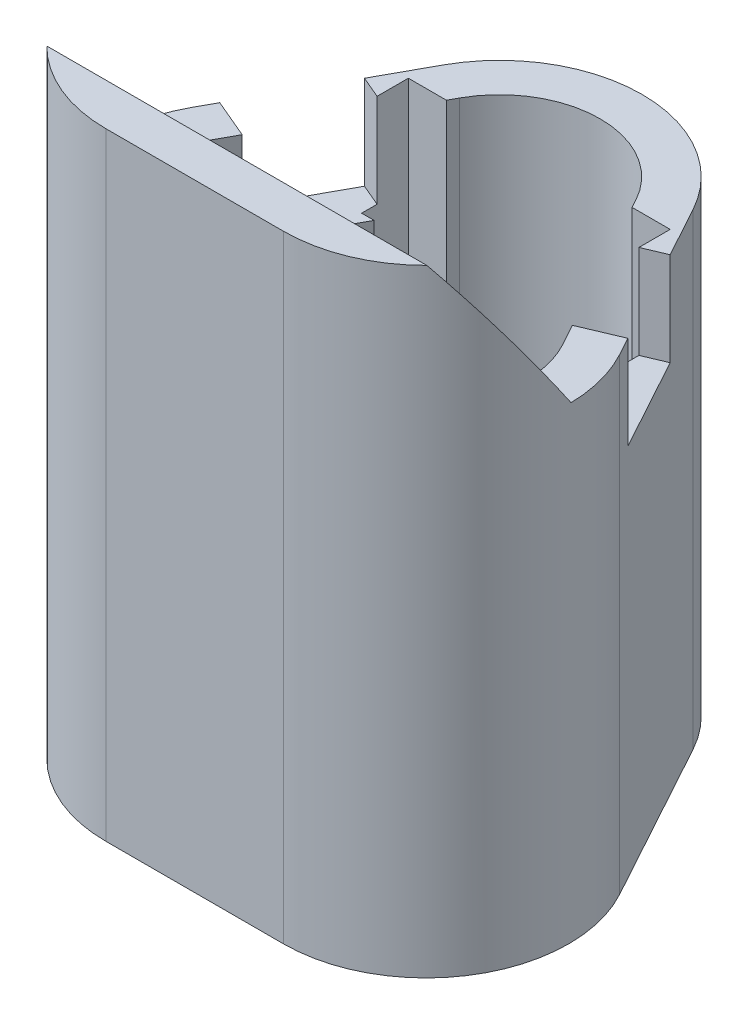
SolidWorks part; units mm, degrees
ref_plane "Plano frontal" through (0, 0, 0) normal (0, 0, 1) x (1, 0, 0)
ref_plane "Plano superior" through (0, 0, 0) normal (0, 1, 0) x (1, 0, 0)
ref_plane "Plano direito" through (0, 0, 0) normal (1, 0, 0) x (0, 0, -1)
sketch "Esboço1" plane through (0, 0, 0) normal (0, 1, 0) x (1, 0, 0)
  line L7 (-13.3761, 16.0541) -> (-22.8761, -1.2959)
  line L8 (13.3761, 16.0541) -> (22.8761, -1.2959)
  line L9 (-9.5, -23.87) -> (9.5, -23.87)
  arc A1 (-22.8761, -1.2959) -> (-9.5, -23.87) centre (-9.5, -8.62) ccw
  arc A3 (9.5, -23.87) -> (22.8761, -1.2959) centre (9.5, -8.62) ccw
  arc A5 (13.3761, 16.0541) -> (-13.3761, 16.0541) centre (0, 8.73) ccw
extrude "Ressalto-extrusão1" add sketch "Esboço1" along normal blind 66 contours L7 A1 L9 A3 L8 A5
sketch "Esboço2" plane through (0, 66, 0) normal (0, 1, 0) x (1, 0, 0)
  line L0 (-18.9291, -3.4571) -> (-9.4291, 13.8929)
  line L1 (18.9291, -3.4571) -> (9.4291, 13.8929)
  line L2 (-9.5, -19.37) -> (9.5, -19.37)
  arc A4 (-18.9291, -3.4571) -> (-9.5, -19.37) centre (-9.5, -8.62) ccw
  arc A6 (9.5, -19.37) -> (18.9291, -3.4571) centre (9.5, -8.62) ccw
  arc A9 (9.4291, 13.8929) -> (-9.4291, 13.8929) centre (0, 8.73) ccw
extrude "Corte-extrusão1" cut sketch "Esboço2" against normal blind 53.5
sketch "Esboço3" plane through (0, 66, 0) normal (0, 1, 0) x (1, 0, 0)
  line L2 (0, -3.37) -> (18.8814, -3.37)
  line L3 (0, -3.37) -> (-18.8814, -3.37)
  line L4 (-9.4291, 13.8929) -> (-18.8814, -3.37)
  line L5 (18.8814, -3.37) -> (9.4291, 13.8929)
  arc A3 (9.4291, 13.8929) -> (-9.4291, 13.8929) centre (0, 8.73) ccw
extrude "Corte-extrusão2" cut sketch "Esboço3" against normal blind 63
sketch "Esboço4" plane through (0, 0, 0) normal (1, 0, 0) x (0, 0, -1)
  line L0 (-8.37, 50) -> (35.3375, 50)
  line L6 (-19.37, 66) -> (-19.37, 68.6327)
  line L7 (-19.37, 68.6327) -> (33.499, 68.6327)
  line L8 (33.499, 68.6327) -> (35.3375, 50)
  line L9 (-19.37, 66) -> (-8.37, 50)
extrude "Corte-extrusão3" cut sketch "Esboço4" against normal through all both and the other way through all
sketch "Esboço5" plane through (0, 50, 0) normal (0, 1, 0) x (1, 0, 0)
  line L2 (5, 11.13) -> (7, 11.13)
  line L3 (7, 11.13) -> (7, 3.13)
  line L4 (7, 3.13) -> (5, 3.13)
  line L5 (5, 3.13) -> (5, 11.13)
  line L7 (-5, 11.13) -> (-5, 3.13)
  line L8 (-5, 3.13) -> (-7, 3.13)
  line L9 (-7, 3.13) -> (-7, 11.13)
  line L10 (-5, 11.13) -> (-7, 11.13)
extrude "Corte-extrusão4" cut sketch "Esboço5" against normal through all both
sketch "Esboço6" plane through (0, 50, 0) normal (0, 1, 0) x (1, 0, 0)
  line L1 (0, 12.98) -> (14, 12.98)
  line L2 (14, 12.98) -> (14, 7.98)
  line L3 (14, 7.98) -> (-14, 7.98)
  line L4 (-14, 7.98) -> (-14, 12.98)
  line L5 (-14, 12.98) -> (0, 12.98)
extrude "Corte-extrusão5" cut sketch "Esboço6" against normal blind 47
sketch "Esboço7" plane through (0, 50, 0) normal (0, 1, 0) x (1, 0, 0)
  line L0 (0, 3.701) -> (16.3461, 10.63)
  line L3 (0, 3.701) -> (-16.3461, 10.63)
  line L9 (-21.8216, 0.63) -> (-16.3461, 10.63)
  line L11 (16.3461, 10.63) -> (21.8216, 0.63)
  line L15 (0, -8.62) -> (-21.8216, 0.63)
  line L16 (0, -8.62) -> (21.8216, 0.63)
extrude "Corte-extrusão7" cut sketch "Esboço7" against normal blind 10
